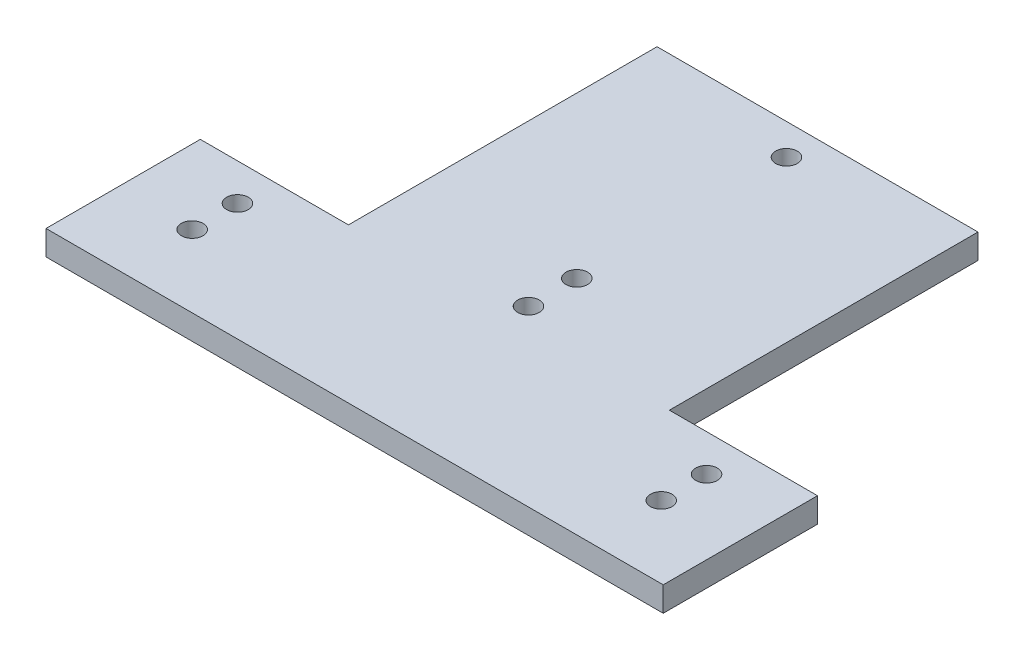
SolidWorks part; units mm, degrees
ref_plane "Alzado" through (0, 0, 0) normal (0, 0, 1) x (1, 0, 0)
ref_plane "Planta" through (0, 0, 0) normal (0, 1, 0) x (1, 0, 0)
ref_plane "Vista lateral" through (0, 0, 0) normal (1, 0, 0) x (0, 0, -1)
sketch "Croquis1" plane through (0, 0, 0) normal (0, 1, 0) x (1, 0, 0)
  line L0 (-50, -12.5) -> (-26, -12.5)
  line L1 (-50, 37.5) -> (50, 37.5)
  line L2 (-50, 37.5) -> (-50, -37.5)
  line L3 (-50, -37.5) -> (50, -37.5)
  line L4 (50, 37.5) -> (50, -37.5)
  line L5 (-50, 37.5) -> (50, -37.5) construction
  line L6 (-50, -37.5) -> (50, 37.5) construction
  line L7 (-26, -12.5) -> (-26, 37.5)
  line L8 (0, 0) -> (0, -18.4798) construction
  line L9 (26, -12.5) -> (26, 37.5)
  line L10 (50, -12.5) -> (26, -12.5)
  circle A0 centre (28.55, -1.5041) radius 1.75
  circle A1 centre (-28.55, -1.5041) radius 1.75
  circle A2 centre (0, -1.5041) radius 1.75
  circle A3 centre (0, -9.3293) radius 1.75
  circle A4 centre (-38, -18.4798) radius 1.75
  circle A5 centre (-38, -25.8161) radius 1.75
  circle A6 centre (38, -25.8161) radius 1.75
  circle A7 centre (38, -18.4798) radius 1.75
  circle A8 centre (0, 32.4638) radius 1.75
  point P0 (0, 0)
  point P30 (0, 32.4638)
  dimension "D5" = 3.5
  dimension "D6" = 3.5
  dimension "D7" = 3.5
  dimension "D8" = 3.5
  dimension "D9" = 3.5
  dimension "D10" = 3.5
  dimension "D11" = 3.5
  dimension "D1" = 75
  dimension "D2" = 100
  dimension "D3" = 50
  dimension "D4" = 24
extrude "Saliente-Extruir1" add sketch "Croquis1" along normal blind 4 contours L4 L10 L9 L1 L7 L0 L2 L3
